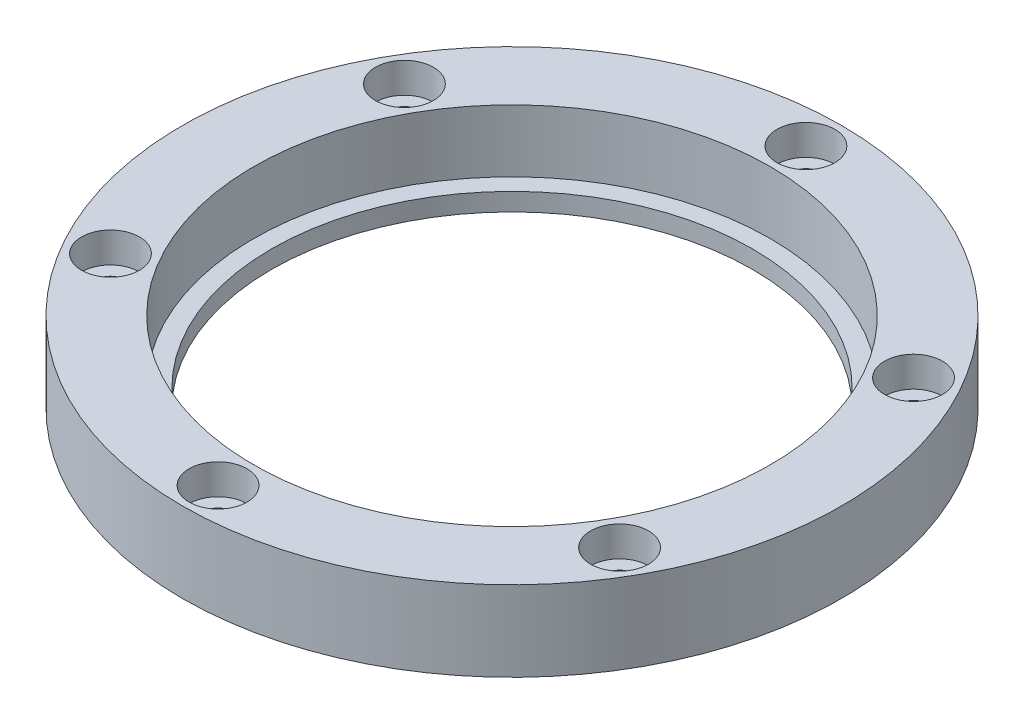
SolidWorks part; units mm, degrees
ref_plane "Ebene vorne" through (0, 0, 0) normal (0, 0, 1) x (1, 0, 0)
ref_plane "Ebene oben" through (0, 0, 0) normal (0, 1, 0) x (1, 0, 0)
ref_plane "Ebene rechts" through (0, 0, 0) normal (1, 0, 0) x (0, 0, -1)
sketch "Sketch1" plane through (0, 0, 0) normal (0, 0, 1) x (1, 0, 0)
  line L0 (0, 0) -> (0, 50) construction
  line L1 (27, 0) -> (37, 0)
  line L2 (37, 0) -> (37, 9)
  line L3 (37, 9) -> (29, 9)
  line L4 (29, 9) -> (29, 2)
  line L5 (29, 2) -> (27, 2)
  line L6 (27, 2) -> (27, 0)
  dimension "D1" = 50
  dimension "D2" = 2
  dimension "D3" = 8
  dimension "D4" = 7
  dimension "D5" = 2
  dimension "D6" = 58
revolve "Revolve1" add sketch "Sketch1" angle 360 about L0
hole_wizard "CBORE for M3 Hex Socket Head Cap Screw1" positions "Sketch3" profile "Sketch4" counterbore size "M3" standard "DIN" end condition through all
sketch "Sketch3" plane through (0, 9, 0) normal (0, 1, 0) x (1, 0, 0)
  line L0 (0, -29) -> (0, -37) construction
  circle A0 centre (0, 0) radius 29 construction
  circle A1 centre (0, 0) radius 29 construction
  circle A2 centre (0, 0) radius 37 construction
  point P10 (0, -33)
  point P17 (-28.5788, -16.5)
  point P18 (-28.5788, 16.5)
  point P19 (0, 33)
  point P20 (28.5788, 16.5)
  point P21 (28.5788, -16.5)
  dimension "D1" = 6
sketch "Sketch4" plane through (28.5788, 9, 16.5) normal (1, 0, 0) x (0, 0, 1)
  line L0 (0, 0) -> (0, 9)
  line L1 (0, 9) -> (1.7, 9)
  line L3 (1.7, 9) -> (1.7, 3.4)
  line L4 (1.7, 3.4) -> (3.25, 3.4)
  line L5 (3.25, 3.4) -> (3.25, 0)
  line L7 (3.25, 0) -> (0, 0)
  line L11 (0, -6.35) -> (0, 107.95) construction
  dimension "Thru Hole Dia." = 3.4
  dimension "Thru Hole Depth" = 9
  dimension "C'Bore Dia." = 6.5
  dimension "C'Bore Depth" = 3.4
